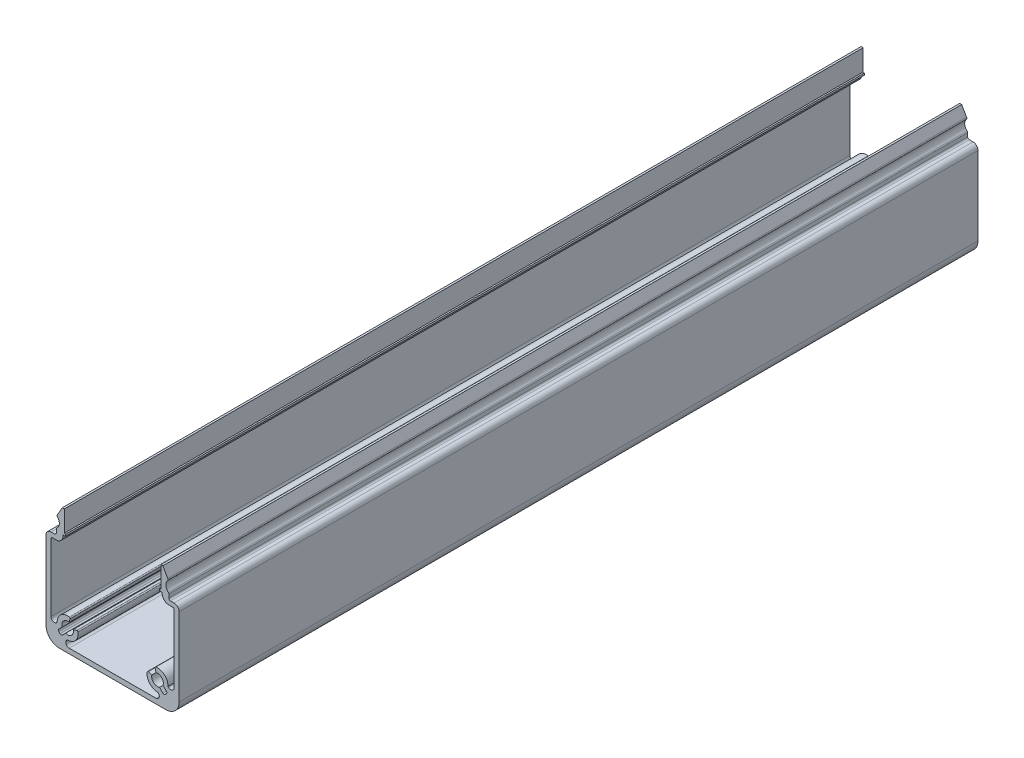
SolidWorks part; units mm, degrees
ref_plane "Front Plane" through (0, 0, 0) normal (0, 0, 1) x (1, 0, 0)
ref_plane "Top Plane" through (0, 0, 0) normal (0, 1, 0) x (1, 0, 0)
ref_plane "Right Plane" through (0, 0, 0) normal (1, 0, 0) x (0, 0, -1)
ref_plane "Plane1" through (0, 0, 20) normal (0, 0, 1) x (1, 0, 0)
sketch "Sketch1" plane through (0, 0, 20) normal (0, 0, 1) x (1, 0, 0)
  line L0 (4, 0) -> (36, 0)
  line L1 (40, 4) -> (40, 27.5)
  line L2 (38.5, 29) -> (37.4085, 29)
  line L3 (36.9085, 29.5) -> (36.9085, 30.572)
  line L4 (36.583, 34.4315) -> (35.1, 37)
  line L5 (35.1, 37) -> (34.5, 37)
  line L6 (34.5, 37) -> (34.5, 30.6727)
  line L7 (34.5, 30.6727) -> (34.1585, 30.5611)
  line L8 (34.1585, 30.5611) -> (34.1585, 29.9899)
  line L9 (34.1585, 29.9899) -> (34.9085, 29.9899)
  line L10 (34.9085, 29.9899) -> (34.9085, 29.7)
  line L11 (36.9085, 27.7) -> (38, 27.7)
  line L12 (38.5, 27.2) -> (38.5, 6.9548)
  line L13 (36.7929, 6.2477) -> (36.6482, 6.3924)
  line L14 (32.7665, 9.2376) -> (33.0471, 8.1904)
  line L15 (35.1484, 5.9123) -> (36.1464, 4.9142)
  line L16 (36.1464, 4.2071) -> (35.7929, 3.8536)
  line L17 (35.0858, 3.8536) -> (34.0877, 4.8516)
  line L18 (31.8096, 6.9529) -> (30.7624, 7.2335)
  line L19 (33.6076, 3.3518) -> (33.7523, 3.2071)
  line L20 (33.0452, 1.5) -> (6.9548, 1.5)
  line L21 (6.2477, 3.2071) -> (6.3924, 3.3518)
  line L22 (9.2376, 7.2335) -> (8.1904, 6.9529)
  line L23 (5.9123, 4.8516) -> (4.9142, 3.8536)
  line L24 (4.2071, 3.8536) -> (3.8536, 4.2071)
  line L25 (3.8536, 4.9142) -> (4.8516, 5.9123)
  line L26 (6.9529, 8.1904) -> (7.2335, 9.2376)
  line L27 (3.3518, 6.3924) -> (3.2071, 6.2477)
  line L28 (1.5, 6.9548) -> (1.5, 27.2)
  line L29 (2, 27.7) -> (3.0915, 27.7)
  line L30 (5.0915, 29.7) -> (5.0915, 29.9899)
  line L31 (5.0915, 29.9899) -> (5.8415, 29.9899)
  line L32 (5.8415, 29.9899) -> (5.8415, 30.5611)
  line L33 (5.8415, 30.5611) -> (5.5, 30.6727)
  line L34 (5.5, 30.6727) -> (5.5, 37)
  line L35 (5.5, 37) -> (4.9, 37)
  line L36 (4.9, 37) -> (3.417, 34.4315)
  line L37 (3.0915, 30.572) -> (3.0915, 29.5)
  line L38 (2.5915, 29) -> (1.5, 29)
  line L39 (0, 27.5) -> (0, 4)
  arc A0 (36, 0) -> (40, 4) centre (36, 4) ccw
  arc A1 (40, 27.5) -> (38.5, 29) centre (38.5, 27.5) ccw
  arc A2 (37.4085, 29) -> (36.9085, 29.5) centre (37.4085, 29.5) cw
  arc A3 (36.9085, 30.572) -> (36.7268, 30.9576) centre (36.4085, 30.572) ccw
  arc A4 (36.7268, 30.9576) -> (36.52, 33.8452) centre (38, 32.5) cw
  arc A5 (36.52, 33.8452) -> (36.583, 34.4315) centre (36.1499, 34.1815) ccw
  arc A6 (34.9085, 29.7) -> (36.9085, 27.7) centre (36.9085, 29.7) ccw
  arc A7 (38, 27.7) -> (38.5, 27.2) centre (38, 27.2) cw
  arc A8 (38.5, 6.9548) -> (36.7929, 6.2477) centre (37.5, 6.9548) cw
  arc A9 (36.6482, 6.3924) -> (33.0095, 9.6116) centre (33.5, 6.5) ccw
  arc A10 (33.0095, 9.6116) -> (32.7665, 9.2376) centre (33.0562, 9.3152) ccw
  arc A11 (33.0471, 8.1904) -> (35.1484, 5.9123) centre (33.5, 6.5) cw
  arc A12 (36.1464, 4.9142) -> (36.1464, 4.2071) centre (35.7929, 4.5607) cw
  arc A13 (35.7929, 3.8536) -> (35.0858, 3.8536) centre (35.4393, 4.2071) cw
  arc A14 (34.0877, 4.8516) -> (31.8096, 6.9529) centre (33.5, 6.5) cw
  arc A15 (30.7624, 7.2335) -> (30.3884, 6.9905) centre (30.6848, 6.9438) ccw
  arc A16 (30.3884, 6.9905) -> (33.6076, 3.3518) centre (33.5, 6.5) ccw
  arc A17 (33.7523, 3.2071) -> (33.0452, 1.5) centre (33.0452, 2.5) cw
  arc A18 (6.9548, 1.5) -> (6.2477, 3.2071) centre (6.9548, 2.5) cw
  arc A19 (6.3924, 3.3518) -> (9.6116, 6.9905) centre (6.5, 6.5) ccw
  arc A20 (9.6116, 6.9905) -> (9.2376, 7.2335) centre (9.3152, 6.9438) ccw
  arc A21 (8.1904, 6.9529) -> (5.9123, 4.8516) centre (6.5, 6.5) cw
  arc A22 (4.9142, 3.8536) -> (4.2071, 3.8536) centre (4.5607, 4.2071) cw
  arc A23 (3.8536, 4.2071) -> (3.8536, 4.9142) centre (4.2071, 4.5607) cw
  arc A24 (4.8516, 5.9123) -> (6.9529, 8.1904) centre (6.5, 6.5) cw
  arc A25 (7.2335, 9.2376) -> (6.9905, 9.6116) centre (6.9438, 9.3152) ccw
  arc A26 (6.9905, 9.6116) -> (3.3518, 6.3924) centre (6.5, 6.5) ccw
  arc A27 (3.2071, 6.2477) -> (1.5, 6.9548) centre (2.5, 6.9548) cw
  arc A28 (1.5, 27.2) -> (2, 27.7) centre (2, 27.2) cw
  arc A29 (3.0915, 27.7) -> (5.0915, 29.7) centre (3.0915, 29.7) ccw
  arc A30 (3.417, 34.4315) -> (3.48, 33.8452) centre (3.8501, 34.1815) ccw
  arc A31 (3.48, 33.8452) -> (3.2732, 30.9576) centre (2, 32.5) cw
  arc A32 (3.2732, 30.9576) -> (3.0915, 30.572) centre (3.5915, 30.572) ccw
  arc A33 (3.0915, 29.5) -> (2.5915, 29) centre (2.5915, 29.5) cw
  arc A34 (1.5, 29) -> (0, 27.5) centre (1.5, 27.5) ccw
  arc A35 (0, 4) -> (4, 0) centre (4, 4) ccw
extrude "Boss-Extrude1" add sketch "Sketch1" against normal blind 240
